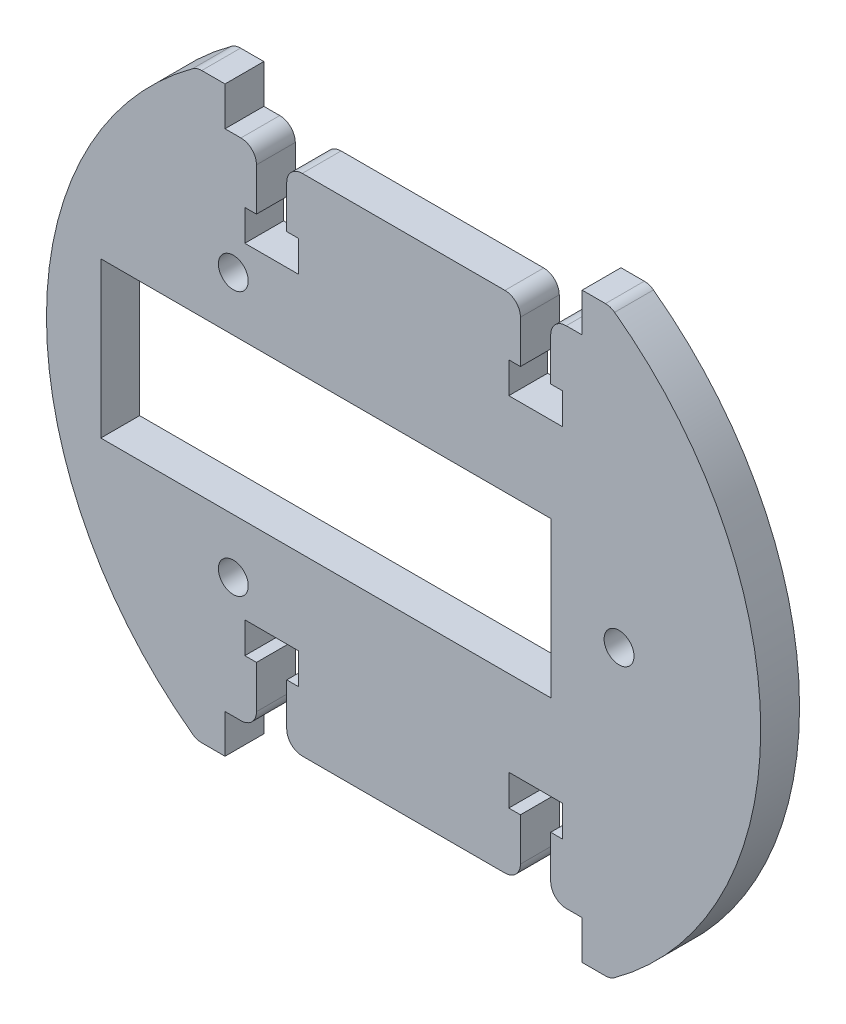
SolidWorks part; units mm, degrees
ref_plane "Plan de face" through (0, 0, 0) normal (0, 0, 1) x (1, 0, 0)
ref_plane "Plan de dessus" through (0, 0, 0) normal (0, 1, 0) x (1, 0, 0)
ref_plane "Plan de droite" through (0, 0, 0) normal (1, 0, 0) x (0, 0, -1)
sketch "Esquisse1" plane through (0, 0, 0) normal (0, 0, 1) x (1, 0, 0)
  line L0 (-21.9331, -17) -> (-21.9331, 17) construction
  line L2 (0, 0) -> (-21.9331, 0) construction
  line L3 (18.95, 30.5) -> (15.05, 30.5) construction
  line L4 (17, 21) -> (17, 30.5) construction
  line L5 (13.05, 32.5) -> (-13.05, 32.5)
  line L6 (15.05, 30.5) -> (15.05, 25)
  line L7 (15.05, 25) -> (13.55, 25)
  line L8 (13.55, 25) -> (13.55, 21)
  line L9 (26, -37.4976) -> (23, -37.5)
  line L10 (23, -37.5) -> (23, -32.5)
  line L11 (23, -32.5) -> (20.95, -32.5)
  line L12 (18.95, -25) -> (18.95, -30.5)
  line L13 (20.45, -25) -> (18.95, -25)
  line L14 (20.45, -21) -> (20.45, -25)
  line L15 (13.55, -21) -> (20.45, -21)
  line L16 (13.55, -25) -> (13.55, -21)
  line L17 (15.05, -25) -> (13.55, -25)
  line L18 (15.05, -30.5) -> (15.05, -25)
  line L19 (13.05, -32.5) -> (-13.05, -32.5)
  line L20 (17, -21) -> (17, -30.5) construction
  line L21 (18.95, -30.5) -> (15.05, -30.5) construction
  line L22 (0, 0) -> (46, 0) construction
  line L23 (13.55, 21) -> (20.45, 21)
  line L24 (20.45, 21) -> (20.45, 25)
  line L25 (20.45, 25) -> (18.95, 25)
  line L26 (18.95, 25) -> (18.95, 30.5)
  line L27 (23, 32.5) -> (20.95, 32.5)
  line L28 (23, 37.5) -> (23, 32.5)
  line L29 (26, 37.4976) -> (23, 37.5)
  line L30 (-18.95, -30.5) -> (-15.05, -30.5) construction
  line L31 (-17, -21) -> (-17, -30.5) construction
  line L32 (-15.05, -30.5) -> (-15.05, -25)
  line L33 (-15.05, -25) -> (-13.55, -25)
  line L34 (-13.55, -25) -> (-13.55, -21)
  line L35 (-13.55, -21) -> (-20.45, -21)
  line L36 (-20.45, -21) -> (-20.45, -25)
  line L37 (-20.45, -25) -> (-18.95, -25)
  line L38 (-18.95, -25) -> (-18.95, -30.5)
  line L39 (-23, -32.5) -> (-20.95, -32.5)
  line L40 (-23, -37.5) -> (-23, -32.5)
  line L41 (-39, 10) -> (19, 10)
  line L42 (-39, 10) -> (-39, -10)
  line L43 (-39, -10) -> (19, -10)
  line L44 (19, 10) -> (19, -10)
  line L47 (-26, -37.4976) -> (-23, -37.5)
  line L52 (-17, 21) -> (-17, 30.5) construction
  line L53 (-18.95, 30.5) -> (-15.05, 30.5) construction
  line L54 (-26, 37.4976) -> (-23, 37.5)
  line L55 (-23, 37.5) -> (-23, 32.5)
  line L56 (0, -32.5) -> (0, 32.5) construction
  line L57 (-23, 32.5) -> (-20.95, 32.5)
  line L58 (-18.95, 25) -> (-18.95, 30.5)
  line L59 (-20.45, 25) -> (-18.95, 25)
  line L60 (-20.45, 21) -> (-20.45, 25)
  line L61 (-13.55, 21) -> (-20.45, 21)
  line L62 (-13.55, 25) -> (-13.55, 21)
  line L63 (-15.05, 25) -> (-13.55, 25)
  line L64 (-15.05, 30.5) -> (-15.05, 25)
  circle A0 centre (27.75, 0) radius 1.925
  circle A1 centre (-21.9331, -17) radius 1.925
  circle A2 centre (-21.9331, 17) radius 1.925
  arc A4 (27.1802, -37.1112) -> (27.1802, 37.1112) centre (0, 0) ccw
  arc A6 (13.05, 32.5) -> (15.05, 30.5) centre (13.05, 30.5) cw
  arc A7 (26, -37.4976) -> (27.1802, -37.1112) centre (25.9984, -35.4976) ccw
  arc A8 (18.95, -30.5) -> (20.95, -32.5) centre (20.95, -30.5) ccw
  arc A9 (13.05, -32.5) -> (15.05, -30.5) centre (13.05, -30.5) ccw
  arc A10 (18.95, 30.5) -> (20.95, 32.5) centre (20.95, 30.5) cw
  arc A11 (26, 37.4976) -> (27.1802, 37.1112) centre (25.9984, 35.4976) cw
  arc A12 (-13.05, -32.5) -> (-15.05, -30.5) centre (-13.05, -30.5) cw
  arc A13 (-18.95, -30.5) -> (-20.95, -32.5) centre (-20.95, -30.5) cw
  arc A14 (-26, -37.4976) -> (-27.1802, -37.1112) centre (-25.9984, -35.4976) cw
  arc A15 (-27.1802, -37.1112) -> (-27.1802, 37.1112) centre (0, 0) cw
  arc A16 (-26, 37.4976) -> (-27.1802, 37.1112) centre (-25.9984, 35.4976) ccw
  arc A17 (-18.95, 30.5) -> (-20.95, 32.5) centre (-20.95, 30.5) ccw
  arc A23 (-13.05, 32.5) -> (-15.05, 30.5) centre (-13.05, 30.5) ccw
  dimension "D5" = 3.85
  dimension "D6" = 46
  dimension "D7" = 34
  dimension "D8" = 2
  dimension "D13" = 2
  dimension "D14" = 2
  dimension "D2" = 32.5
  dimension "D4" = 20
  dimension "D9" = 11.5
  dimension "D10" = 7.5
  dimension "D11" = 6.9
  dimension "D12" = 3.9
  dimension "D15" = 13.55
  dimension "D16" = 5.5
  dimension "D17" = 58
  dimension "D18" = 19
  dimension "D19" = 10
  dimension "D26" = 21.9331
  dimension "D33" = 27.75
  dimension "D37" = 5
  dimension "D38" = 6
  dimension "D39" = 3
extrude "Boss.-Extru.1" add sketch "Esquisse1" along normal blind 5
